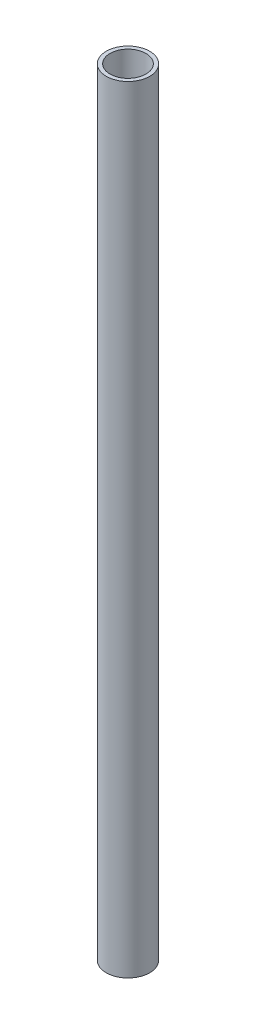
SolidWorks part; units mm, degrees
ref_plane "정면" through (0, 0, 0) normal (0, 0, 1) x (1, 0, 0)
ref_plane "윗면" through (0, 0, 0) normal (0, 1, 0) x (1, 0, 0)
ref_plane "우측면" through (0, 0, 0) normal (1, 0, 0) x (0, 0, -1)
sketch "스케치1" plane through (0, 0, 0) normal (0, 1, 0) x (1, 0, 0)
  circle A0 centre (0, 0) radius 12.6
  dimension "D1" = 25.2
extrude "보스-돌출1" add sketch "스케치1" along normal blind 450
shell "쉘1" thickness 2.2
